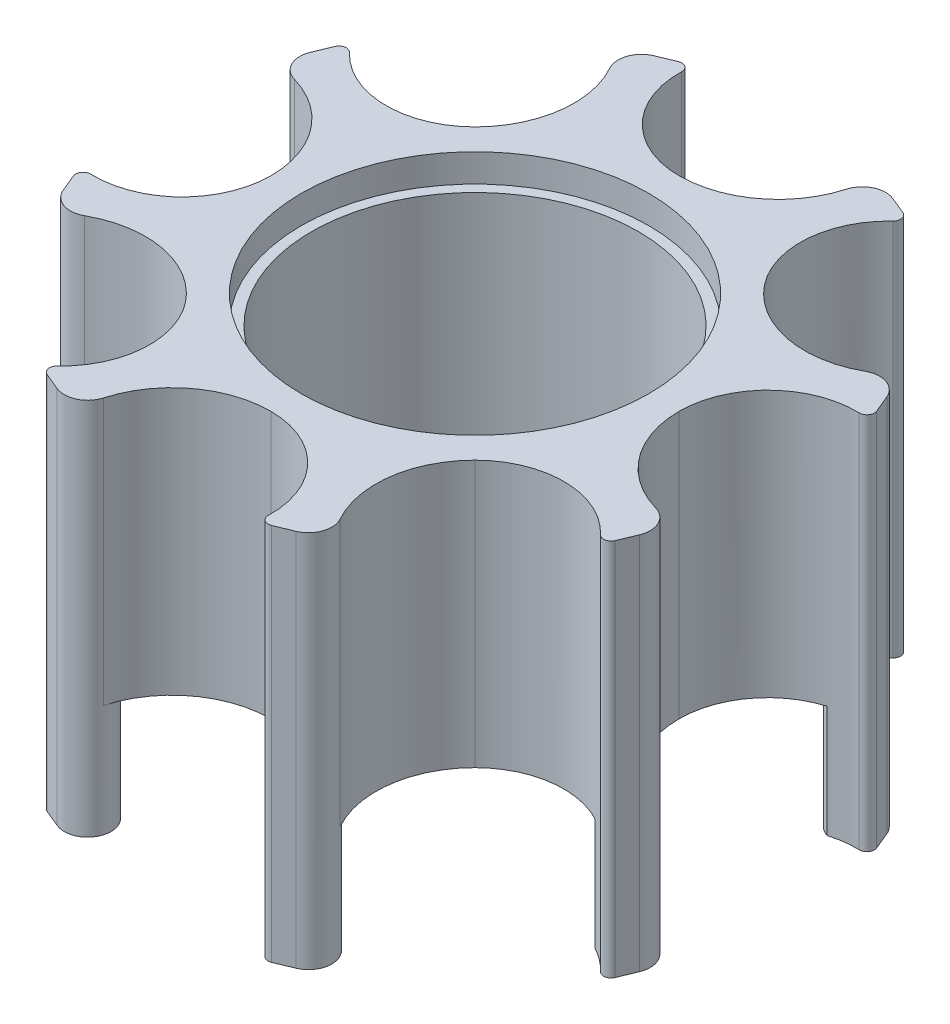
SolidWorks part; units mm, degrees
ref_plane "前视基准面" through (0, 0, 0) normal (0, 0, 1) x (1, 0, 0)
ref_plane "上视基准面" through (0, 0, 0) normal (0, 1, 0) x (1, 0, 0)
ref_plane "右视基准面" through (0, 0, 0) normal (1, 0, 0) x (0, 0, -1)
sketch "草图1" plane through (0, 0, 0) normal (0, 1, 0) x (1, 0, 0)
  line L0 (0, 31.36) -> (22.1749, 22.1749) construction
  line L1 (22.1749, 22.1749) -> (11.6426, 26.5375) construction
  line L2 (11.6426, 26.5375) -> (12.609, 28.8706) construction
  line L3 (11.6426, 26.5375) -> (14.0958, 32.46) construction
  line L4 (13.5658, 31.1803) -> (21.3089, 27.973) construction
  line L5 (13.5658, 31.1803) -> (15.4095, 30.4166)
  line L6 (31.6402, 12.4553) -> (32.4039, 10.6116)
  line L7 (31.1803, -13.5658) -> (30.4166, -15.4095)
  line L8 (12.4553, -31.6402) -> (10.6116, -32.4039)
  line L9 (-13.5658, -31.1803) -> (-15.4095, -30.4166)
  line L10 (-31.6402, -12.4553) -> (-32.4039, -10.6116)
  line L11 (-31.1803, 13.5658) -> (-30.4166, 15.4095)
  line L12 (-12.4553, 31.6402) -> (-10.6116, 32.4039)
  circle A0 centre (0, 0) radius 40.9 construction
  circle A1 centre (0, 0) radius 32.46 construction
  circle A11 centre (0, 0) radius 31.36 construction
  arc A13 (15.652, 29.0953) -> (15.4503, 15.4503) centre (22.1749, 22.1749) ccw
  arc A20 (13.5658, 31.1803) -> (10.2046, 29.5551) centre (12.609, 28.8706) ccw
  arc A21 (0, 21.85) -> (10.2046, 29.5551) centre (0, 32.46) ccw
  arc A23 (15.4503, 15.4503) -> (28.1143, 13.6829) centre (22.9527, 22.9527) ccw
  arc A24 (15.652, 29.0953) -> (15.4095, 30.4166) centre (15.1033, 29.6775) ccw
  arc A26 (31.6402, 12.4553) -> (28.1143, 13.6829) centre (29.3305, 11.4986) ccw
  arc A27 (31.6412, 9.5058) -> (32.4039, 10.6116) centre (31.6648, 10.3055) ccw
  arc A28 (31.6412, 9.5058) -> (21.85, 0) centre (31.36, 0) ccw
  arc A29 (21.85, 0) -> (29.5551, -10.2046) centre (32.46, 0) ccw
  arc A30 (31.1803, -13.5658) -> (29.5551, -10.2046) centre (28.8706, -12.609) ccw
  arc A31 (29.0953, -15.652) -> (30.4166, -15.4095) centre (29.6775, -15.1033) ccw
  arc A32 (29.0953, -15.652) -> (15.4503, -15.4503) centre (22.1749, -22.1749) ccw
  arc A33 (15.4503, -15.4503) -> (13.6829, -28.1143) centre (22.9527, -22.9527) ccw
  arc A34 (12.4553, -31.6402) -> (13.6829, -28.1143) centre (11.4986, -29.3305) ccw
  arc A35 (9.5058, -31.6412) -> (10.6116, -32.4039) centre (10.3055, -31.6648) ccw
  arc A36 (9.5058, -31.6412) -> (0, -21.85) centre (0, -31.36) ccw
  arc A37 (0, -21.85) -> (-10.2046, -29.5551) centre (0, -32.46) ccw
  arc A38 (-13.5658, -31.1803) -> (-10.2046, -29.5551) centre (-12.609, -28.8706) ccw
  arc A39 (-15.652, -29.0953) -> (-15.4095, -30.4166) centre (-15.1033, -29.6775) ccw
  arc A40 (-15.652, -29.0953) -> (-15.4503, -15.4503) centre (-22.1749, -22.1749) ccw
  arc A41 (-15.4503, -15.4503) -> (-28.1143, -13.6829) centre (-22.9527, -22.9527) ccw
  arc A42 (-31.6402, -12.4553) -> (-28.1143, -13.6829) centre (-29.3305, -11.4986) ccw
  arc A43 (-31.6412, -9.5058) -> (-32.4039, -10.6116) centre (-31.6648, -10.3055) ccw
  arc A44 (-31.6412, -9.5058) -> (-21.85, 0) centre (-31.36, 0) ccw
  arc A45 (-21.85, 0) -> (-29.5551, 10.2046) centre (-32.46, 0) ccw
  arc A46 (-31.1803, 13.5658) -> (-29.5551, 10.2046) centre (-28.8706, 12.609) ccw
  arc A47 (-29.0953, 15.652) -> (-30.4166, 15.4095) centre (-29.6775, 15.1033) ccw
  arc A48 (-29.0953, 15.652) -> (-15.4503, 15.4503) centre (-22.1749, 22.1749) ccw
  arc A49 (-15.4503, 15.4503) -> (-13.6829, 28.1143) centre (-22.9527, 22.9527) ccw
  arc A50 (-12.4553, 31.6402) -> (-13.6829, 28.1143) centre (-11.4986, 29.3305) ccw
  arc A51 (-9.5058, 31.6412) -> (-10.6116, 32.4039) centre (-10.3055, 31.6648) ccw
  arc A52 (-9.5058, 31.6412) -> (0, 21.85) centre (0, 31.36) ccw
  dimension "D1" = 81.8
  dimension "D2" = 64.92
  dimension "D3" = 8
  dimension "D4" = 9.51
  dimension "D5" = 0.8
  dimension "D10" = 62.72
  dimension "D12" = 5
  dimension "D9" = 11.4
  dimension "D13" = 2.5253
extrude "凸台-拉伸1" add sketch "草图1" along normal blind 35
sketch "草图5" plane through (0, 35, 0) normal (0, 1, 0) x (1, 0, 0)
  circle A0 centre (0, 0) radius 17.5
  dimension "D1" = 35
extrude "切除-拉伸3" cut sketch "草图5" against normal blind 27.5
sketch "草图6" plane through (0, 35, 0) normal (0, 1, 0) x (1, 0, 0)
  circle A0 centre (0, 0) radius 18.6
  dimension "D1" = 37.2
extrude "切除-拉伸4" cut sketch "草图6" against normal blind 3
sketch "草图7" plane through (0, 0, 0) normal (0, -1, 0) x (1, 0, 0)
  line L8 (13.5658, -31.1803) -> (15.4095, -30.4166)
  line L9 (31.6402, -12.4553) -> (32.4039, -10.6116)
  line L10 (31.1803, 13.5658) -> (30.4166, 15.4095)
  line L11 (12.4553, 31.6402) -> (10.6116, 32.4039)
  line L12 (-13.5658, 31.1803) -> (-15.4095, 30.4166)
  line L13 (-31.6402, 12.4553) -> (-32.4039, 10.6116)
  line L14 (-31.1803, -13.5658) -> (-30.4166, -15.4095)
  line L15 (-12.4553, -31.6402) -> (-10.6116, -32.4039)
  arc A0 (9.1042, 28.6117) -> (13.6829, 28.1143) centre (11.4986, 29.3305) ccw
  arc A2 (26.6692, 13.7938) -> (29.5551, 10.2046) centre (28.8706, 12.609) ccw
  arc A3 (28.6117, -9.1042) -> (28.1143, -13.6829) centre (29.3305, -11.4986) ccw
  arc A4 (13.7938, -26.6692) -> (10.2046, -29.5551) centre (12.609, -28.8706) ccw
  arc A5 (-9.1042, -28.6117) -> (-13.6829, -28.1143) centre (-11.4986, -29.3305) ccw
  arc A6 (-26.6692, -13.7938) -> (-29.5551, -10.2046) centre (-28.8706, -12.609) ccw
  arc A7 (-28.6117, 9.1042) -> (-28.1143, 13.6829) centre (-29.3305, 11.4986) ccw
  arc A8 (-13.7938, 26.6692) -> (-10.2046, 29.5551) centre (-12.609, 28.8706) ccw
  arc A32 (0, -21.85) -> (-9.5058, -31.6412) centre (0, -31.36) ccw
  arc A33 (10.2046, -29.5551) -> (0, -21.85) centre (0, -32.46) ccw
  arc A34 (10.2046, -29.5551) -> (13.5658, -31.1803) centre (12.609, -28.8706) ccw
  arc A35 (15.4095, -30.4166) -> (15.652, -29.0953) centre (15.1033, -29.6775) ccw
  arc A36 (15.4503, -15.4503) -> (15.652, -29.0953) centre (22.1749, -22.1749) ccw
  arc A37 (28.1143, -13.6829) -> (15.4503, -15.4503) centre (22.9527, -22.9527) ccw
  arc A38 (28.1143, -13.6829) -> (31.6402, -12.4553) centre (29.3305, -11.4986) ccw
  arc A39 (32.4039, -10.6116) -> (31.6412, -9.5058) centre (31.6648, -10.3055) ccw
  arc A40 (21.85, 0) -> (31.6412, -9.5058) centre (31.36, 0) ccw
  arc A41 (29.5551, 10.2046) -> (21.85, 0) centre (32.46, 0) ccw
  arc A42 (29.5551, 10.2046) -> (31.1803, 13.5658) centre (28.8706, 12.609) ccw
  arc A43 (30.4166, 15.4095) -> (29.0953, 15.652) centre (29.6775, 15.1033) ccw
  arc A44 (15.4503, 15.4503) -> (29.0953, 15.652) centre (22.1749, 22.1749) ccw
  arc A45 (13.6829, 28.1143) -> (15.4503, 15.4503) centre (22.9527, 22.9527) ccw
  arc A46 (13.6829, 28.1143) -> (12.4553, 31.6402) centre (11.4986, 29.3305) ccw
  arc A47 (10.6116, 32.4039) -> (9.5058, 31.6412) centre (10.3055, 31.6648) ccw
  arc A48 (0, 21.85) -> (9.5058, 31.6412) centre (0, 31.36) ccw
  arc A49 (-10.2046, 29.5551) -> (0, 21.85) centre (0, 32.46) ccw
  arc A50 (-10.2046, 29.5551) -> (-13.5658, 31.1803) centre (-12.609, 28.8706) ccw
  arc A51 (-15.4095, 30.4166) -> (-15.652, 29.0953) centre (-15.1033, 29.6775) ccw
  arc A52 (-15.4503, 15.4503) -> (-15.652, 29.0953) centre (-22.1749, 22.1749) ccw
  arc A53 (-28.1143, 13.6829) -> (-15.4503, 15.4503) centre (-22.9527, 22.9527) ccw
  arc A54 (-28.1143, 13.6829) -> (-31.6402, 12.4553) centre (-29.3305, 11.4986) ccw
  arc A55 (-32.4039, 10.6116) -> (-31.6412, 9.5058) centre (-31.6648, 10.3055) ccw
  arc A56 (-21.85, 0) -> (-31.6412, 9.5058) centre (-31.36, 0) ccw
  arc A57 (-29.5551, -10.2046) -> (-21.85, 0) centre (-32.46, 0) ccw
  arc A58 (-29.5551, -10.2046) -> (-31.1803, -13.5658) centre (-28.8706, -12.609) ccw
  arc A59 (-30.4166, -15.4095) -> (-29.0953, -15.652) centre (-29.6775, -15.1033) ccw
  arc A60 (-15.4503, -15.4503) -> (-29.0953, -15.652) centre (-22.1749, -22.1749) ccw
  arc A61 (-13.6829, -28.1143) -> (-15.4503, -15.4503) centre (-22.9527, -22.9527) ccw
  arc A62 (-13.6829, -28.1143) -> (-12.4553, -31.6402) centre (-11.4986, -29.3305) ccw
  arc A63 (-10.6116, -32.4039) -> (-9.5058, -31.6412) centre (-10.3055, -31.6648) ccw
  arc A64 (0, -21.85) -> (-9.1042, -28.6117) centre (0, -31.36) ccw
  arc A65 (10.2046, -29.5551) -> (0, -21.85) centre (0, -32.46) ccw
  arc A68 (15.4503, -15.4503) -> (13.7938, -26.6692) centre (22.1749, -22.1749) ccw
  arc A69 (28.1143, -13.6829) -> (15.4503, -15.4503) centre (22.9527, -22.9527) ccw
  arc A72 (21.85, 0) -> (28.6117, -9.1042) centre (31.36, 0) ccw
  arc A73 (29.5551, 10.2046) -> (21.85, 0) centre (32.46, 0) ccw
  arc A76 (15.4503, 15.4503) -> (26.6692, 13.7938) centre (22.1749, 22.1749) ccw
  arc A77 (13.6829, 28.1143) -> (15.4503, 15.4503) centre (22.9527, 22.9527) ccw
  arc A80 (0, 21.85) -> (9.1042, 28.6117) centre (0, 31.36) ccw
  arc A81 (-10.2046, 29.5551) -> (0, 21.85) centre (0, 32.46) ccw
  arc A84 (-15.4503, 15.4503) -> (-13.7938, 26.6692) centre (-22.1749, 22.1749) ccw
  arc A85 (-28.1143, 13.6829) -> (-15.4503, 15.4503) centre (-22.9527, 22.9527) ccw
  arc A88 (-21.85, 0) -> (-28.6117, 9.1042) centre (-31.36, 0) ccw
  arc A89 (-29.5551, -10.2046) -> (-21.85, 0) centre (-32.46, 0) ccw
  arc A92 (-15.4503, -15.4503) -> (-26.6692, -13.7938) centre (-22.1749, -22.1749) ccw
  arc A93 (-13.6829, -28.1143) -> (-15.4503, -15.4503) centre (-22.9527, -22.9527) ccw
  dimension "D2" = 8
  dimension "D1" = 0
extrude "切除-拉伸5" cut sketch "草图7" against normal blind 6.48
sketch "草图8" plane through (0, 6.48, 0) normal (0, -1, 0) x (1, 0, 0)
  line L0 (0, 0) -> (0, 2.5) construction
  line L1 (1.833, 2.5) -> (-1.833, 2.5)
  arc A0 (-1.833, 2.5) -> (1.833, 2.5) centre (0, 0) ccw
  dimension "D1" = 6.2
  dimension "D2" = 2.5
extrude "切除-拉伸6" cut sketch "草图8" against normal through all
sketch "草图11" plane through (0, 0, 0) normal (0, -1, 0) x (1, 0, 0)
  line L0 (31.6402, -12.4553) -> (32.4039, -10.6116) construction
  line L1 (31.1803, 13.5658) -> (30.4166, 15.4095) construction
  line L2 (12.4553, 31.6402) -> (10.6116, 32.4039) construction
  line L3 (-13.5658, 31.1803) -> (-15.4095, 30.4166) construction
  line L4 (-31.6402, 12.4553) -> (-32.4039, 10.6116) construction
  line L5 (-31.1803, -13.5658) -> (-30.4166, -15.4095) construction
  line L6 (-12.4553, -31.6402) -> (-10.6116, -32.4039) construction
  line L7 (13.5658, -31.1803) -> (15.4095, -30.4166) construction
  line L8 (31.6402, -12.4553) -> (32.4039, -10.6116)
  line L9 (31.1803, 13.5658) -> (30.4166, 15.4095)
  line L10 (12.4553, 31.6402) -> (10.6116, 32.4039)
  line L11 (-13.5658, 31.1803) -> (-15.4095, 30.4166)
  line L12 (-31.6402, 12.4553) -> (-32.4039, 10.6116)
  line L13 (-31.1803, -13.5658) -> (-30.4166, -15.4095)
  line L14 (-12.4553, -31.6402) -> (-10.6116, -32.4039)
  line L15 (13.5658, -31.1803) -> (15.4095, -30.4166)
  arc A0 (28.6117, -9.1042) -> (31.6412, -9.5058) centre (31.36, 0) ccw construction
  arc A1 (28.6117, -9.1042) -> (31.6402, -12.4553) centre (29.3305, -11.4986) ccw construction
  arc A2 (32.4039, -10.6116) -> (31.6412, -9.5058) centre (31.6648, -10.3055) ccw construction
  arc A3 (26.6692, 13.7938) -> (29.0953, 15.652) centre (22.1749, 22.1749) ccw construction
  arc A4 (26.6692, 13.7938) -> (31.1803, 13.5658) centre (28.8706, 12.609) ccw construction
  arc A5 (30.4166, 15.4095) -> (29.0953, 15.652) centre (29.6775, 15.1033) ccw construction
  arc A6 (9.1042, 28.6117) -> (9.5058, 31.6412) centre (0, 31.36) ccw construction
  arc A7 (9.1042, 28.6117) -> (12.4553, 31.6402) centre (11.4986, 29.3305) ccw construction
  arc A8 (10.6116, 32.4039) -> (9.5058, 31.6412) centre (10.3055, 31.6648) ccw construction
  arc A9 (-13.7938, 26.6692) -> (-15.652, 29.0953) centre (-22.1749, 22.1749) ccw construction
  arc A10 (-13.7938, 26.6692) -> (-13.5658, 31.1803) centre (-12.609, 28.8706) ccw construction
  arc A11 (-15.4095, 30.4166) -> (-15.652, 29.0953) centre (-15.1033, 29.6775) ccw construction
  arc A12 (-28.6117, 9.1042) -> (-31.6412, 9.5058) centre (-31.36, 0) ccw construction
  arc A13 (-28.6117, 9.1042) -> (-31.6402, 12.4553) centre (-29.3305, 11.4986) ccw construction
  arc A14 (-32.4039, 10.6116) -> (-31.6412, 9.5058) centre (-31.6648, 10.3055) ccw construction
  arc A15 (-26.6692, -13.7938) -> (-29.0953, -15.652) centre (-22.1749, -22.1749) ccw construction
  arc A16 (-26.6692, -13.7938) -> (-31.1803, -13.5658) centre (-28.8706, -12.609) ccw construction
  arc A17 (-30.4166, -15.4095) -> (-29.0953, -15.652) centre (-29.6775, -15.1033) ccw construction
  arc A18 (-9.1042, -28.6117) -> (-9.5058, -31.6412) centre (0, -31.36) ccw construction
  arc A19 (-9.1042, -28.6117) -> (-12.4553, -31.6402) centre (-11.4986, -29.3305) ccw construction
  arc A20 (-10.6116, -32.4039) -> (-9.5058, -31.6412) centre (-10.3055, -31.6648) ccw construction
  arc A21 (13.7938, -26.6692) -> (15.652, -29.0953) centre (22.1749, -22.1749) ccw construction
  arc A22 (13.7938, -26.6692) -> (13.5658, -31.1803) centre (12.609, -28.8706) ccw construction
  arc A23 (15.4095, -30.4166) -> (15.652, -29.0953) centre (15.1033, -29.6775) ccw construction
  arc A24 (28.6117, -9.1042) -> (31.6412, -9.5058) centre (31.36, 0) ccw
  arc A25 (28.6117, -9.1042) -> (31.6402, -12.4553) centre (29.3305, -11.4986) ccw
  arc A26 (32.4039, -10.6116) -> (31.6412, -9.5058) centre (31.6648, -10.3055) ccw
  arc A27 (26.6692, 13.7938) -> (29.0953, 15.652) centre (22.1749, 22.1749) ccw
  arc A28 (26.6692, 13.7938) -> (31.1803, 13.5658) centre (28.8706, 12.609) ccw
  arc A29 (30.4166, 15.4095) -> (29.0953, 15.652) centre (29.6775, 15.1033) ccw
  arc A30 (9.1042, 28.6117) -> (9.5058, 31.6412) centre (0, 31.36) ccw
  arc A31 (9.1042, 28.6117) -> (12.4553, 31.6402) centre (11.4986, 29.3305) ccw
  arc A32 (10.6116, 32.4039) -> (9.5058, 31.6412) centre (10.3055, 31.6648) ccw
  arc A33 (-13.7938, 26.6692) -> (-15.652, 29.0953) centre (-22.1749, 22.1749) ccw
  arc A34 (-13.7938, 26.6692) -> (-13.5658, 31.1803) centre (-12.609, 28.8706) ccw
  arc A35 (-15.4095, 30.4166) -> (-15.652, 29.0953) centre (-15.1033, 29.6775) ccw
  arc A36 (-28.6117, 9.1042) -> (-31.6412, 9.5058) centre (-31.36, 0) ccw
  arc A37 (-28.6117, 9.1042) -> (-31.6402, 12.4553) centre (-29.3305, 11.4986) ccw
  arc A38 (-32.4039, 10.6116) -> (-31.6412, 9.5058) centre (-31.6648, 10.3055) ccw
  arc A39 (-26.6692, -13.7938) -> (-29.0953, -15.652) centre (-22.1749, -22.1749) ccw
  arc A40 (-26.6692, -13.7938) -> (-31.1803, -13.5658) centre (-28.8706, -12.609) ccw
  arc A41 (-30.4166, -15.4095) -> (-29.0953, -15.652) centre (-29.6775, -15.1033) ccw
  arc A42 (-9.1042, -28.6117) -> (-9.5058, -31.6412) centre (0, -31.36) ccw
  arc A43 (-9.1042, -28.6117) -> (-12.4553, -31.6402) centre (-11.4986, -29.3305) ccw
  arc A44 (-10.6116, -32.4039) -> (-9.5058, -31.6412) centre (-10.3055, -31.6648) ccw
  arc A45 (13.7938, -26.6692) -> (15.652, -29.0953) centre (22.1749, -22.1749) ccw
  arc A46 (13.7938, -26.6692) -> (13.5658, -31.1803) centre (12.609, -28.8706) ccw
  arc A47 (15.4095, -30.4166) -> (15.652, -29.0953) centre (15.1033, -29.6775) ccw
extrude "凸台-拉伸2" add sketch "草图11" along normal blind 5.52
sketch "草图12" plane through (0, 6.48, 0) normal (0, -1, 0) x (1, 0, 0)
  circle A0 centre (0, 0) radius 10 construction
  circle A1 centre (10, 0) radius 1.3
  circle A2 centre (0, -10) radius 1.3
  circle A3 centre (-10, 0) radius 1.3
  dimension "D1" = 20
  dimension "D2" = 2.6
extrude "切除-拉伸7" cut sketch "草图12" against normal through all
sketch "草图13" plane through (0, 7.5, 0) normal (0, 1, 0) x (1, 0, 0)
  line L0 (-1.833, -2.5) -> (1.833, -2.5)
  line L1 (-1.833, -2.5) -> (1.833, -2.5) construction
  circle A0 centre (-10, 0) radius 1.3
  circle A1 centre (0, 0) radius 17.5
  circle A2 centre (0, 0) radius 17.5
  circle A3 centre (0, 10) radius 1.3
  circle A4 centre (10, 0) radius 1.3
  arc A5 (1.833, -2.5) -> (-1.833, -2.5) centre (0, 0) ccw construction
  arc A6 (1.833, -2.5) -> (-1.833, -2.5) centre (0, 0) ccw
  dimension "D1" = 0
extrude "凸台-拉伸3" add sketch "草图13" along normal blind 2
